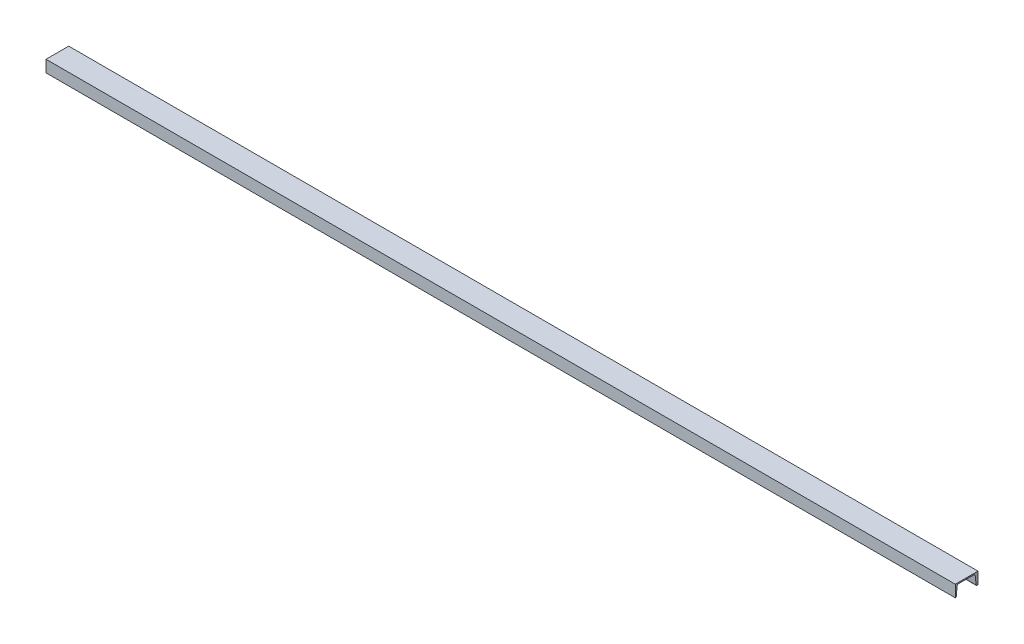
SolidWorks part; units mm, degrees
ref_plane "Front Plane" through (0, 0, 0) normal (0, 0, 1) x (1, 0, 0)
ref_plane "Top Plane" through (0, 0, 0) normal (0, 1, 0) x (1, 0, 0)
ref_plane "Right Plane" through (0, 0, 0) normal (1, 0, 0) x (0, 0, -1)
sketch "Sketch1" plane through (0, 0, 0) normal (0, 0, 1) x (1, 0, 0)
  line L0 (0, 0) -> (-5005, 0)
  dimension "D1" = 5005
other "C channel 120 X 12(1)"
ref_plane "Plane1" through (0, 0, 0) normal (-1, 0, 0) x (0, -1, 0)
sketch "Sketch11" plane through (0, 0, 0) normal (-1, 0, 0) x (0, -1, 0)
  line L0 (65, 125) -> (0, 125)
  line L1 (65, 0) -> (0, 0)
  line L2 (0, 125) -> (0, 0)
  line L6 (65, 125) -> (65, 124.1647)
  line L7 (65, 0) -> (65, 5.8453)
  line L12 (6.3, 106.74) -> (6.3, 23.27)
  line L17 (13.4638, 114.6962) -> (60.9704, 119.6893)
  line L18 (13.4638, 15.3138) -> (60.9704, 10.3207)
  arc A0 (60.9704, 119.6893) -> (65, 124.1647) centre (60.5, 124.1647) ccw
  arc A1 (60.9704, 10.3207) -> (65, 5.8453) centre (60.5, 5.8453) cw
  arc A9 (6.3, 23.27) -> (13.4638, 15.3138) centre (14.3, 23.27) ccw
  arc A10 (6.3, 106.74) -> (13.4638, 114.6962) centre (14.3, 106.74) cw
  point P8 (0, 62.5)
  point P9 (6.3, 65.005)
  point P10 (32.5, 125)
  point P11 (32.5, 0)
  point P12 (65, 9.8971)
  point P13 (65, 120.1129)
  point P14 (0, 0)
  dimension "D4" = 4.5
  dimension "RI" = 8
  dimension "D2" = 6
  dimension "D3" = 18.26
  dimension "Depth" = 125
  dimension "BF" = 65
  dimension "TW" = 6.3
  dimension "d1" = 83.47
